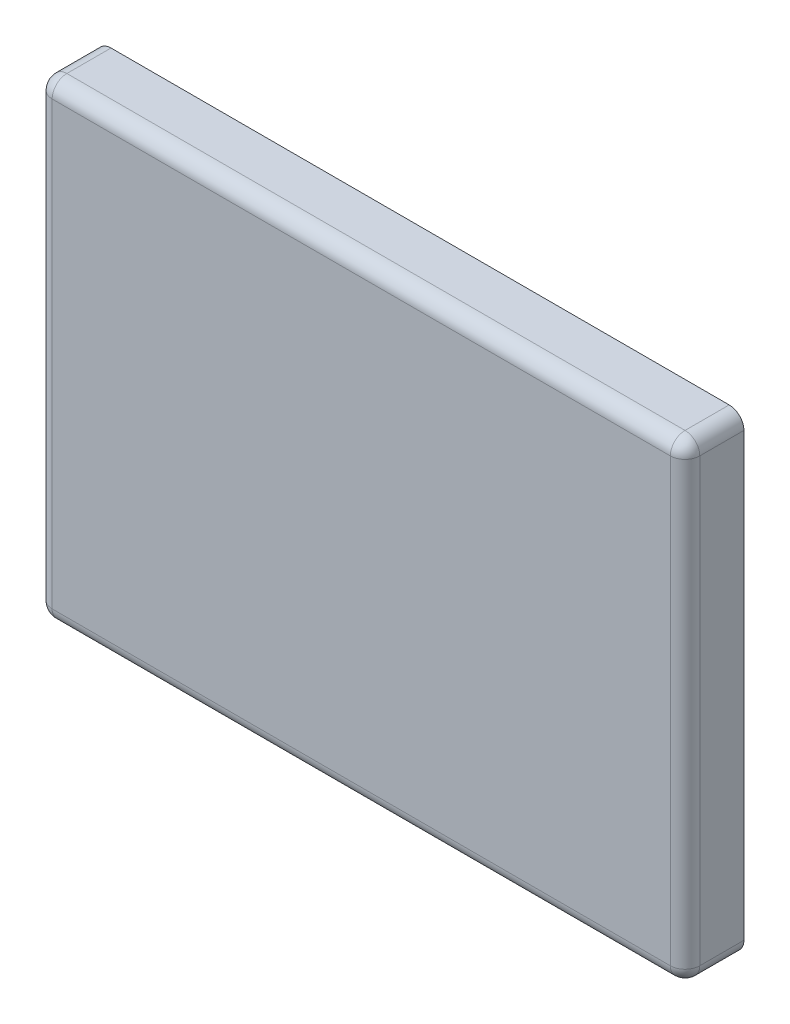
SolidWorks part; units mm, degrees
ref_plane "前视基准面" through (0, 0, 0) normal (0, 0, 1) x (1, 0, 0)
ref_plane "上视基准面" through (0, 0, 0) normal (0, 1, 0) x (1, 0, 0)
ref_plane "右视基准面" through (0, 0, 0) normal (1, 0, 0) x (0, 0, -1)
other "Configuration Table"
sketch "草图1" plane through (0, 0, 0) normal (0, 0, 1) x (1, 0, 0)
  line L1 (0, 0) -> (440, 0)
  line L2 (0, 0) -> (0, -320)
  line L3 (0, -320) -> (440, -320)
  line L4 (440, 0) -> (440, -320)
  dimension "D1" = 440
  dimension "D2" = 320
extrude "凸台-拉伸1" add sketch "草图1" along normal blind 40
fillet "圆角1" radius 10 8 edges at (0, -320, 20) (0, -160, 40) (220, -320, 40) (440, -320, 20) (440, -160, 40) (220, 0, 40) (440, 0, 20) (0, 0, 20)
sketch "草图3" plane through (0, 0, 0) normal (0, 0, -1) x (-1, 0, 0)
  line L0 (0, -10) -> (0, -310) construction
  line L1 (-400, -40) -> (-40, -40)
  line L2 (-400, -40) -> (-400, -280)
  line L3 (-400, -280) -> (-40, -280)
  line L4 (-40, -40) -> (-40, -280)
  line L5 (-10, -320) -> (-430, -320) construction
  line L6 (-430, 0) -> (-10, 0) construction
  line L7 (-440, -310) -> (-440, -10) construction
  dimension "D1" = 40
  dimension "D2" = 40
  dimension "D3" = 40
  dimension "D4" = 40
extrude "凸台-拉伸2" add sketch "草图3" along normal blind 20
sketch "草图4" plane through (0, 0, 0) normal (0, 0, -1) x (-1, 0, 0)
  line L0 (-430, 0) -> (-10, 0) construction
  line L1 (-400, -40) -> (-400, -280) construction
  line L2 (-10, -320) -> (-430, -320) construction
  line L4 (-400, -40) -> (-400, -280) construction
  circle A0 centre (-430, -60) radius 5
  circle A1 centre (-430, -260) radius 5
  point P11 (-430, -60)
  point P13 (-430, -260)
  dimension "D1" = 10
  dimension "D2" = 10
  dimension "D3" = 60
  dimension "D4" = 30
  dimension "D5" = 60
  dimension "D6" = 30
extrude "切除-拉伸1" cut sketch "草图4" against normal blind 10
